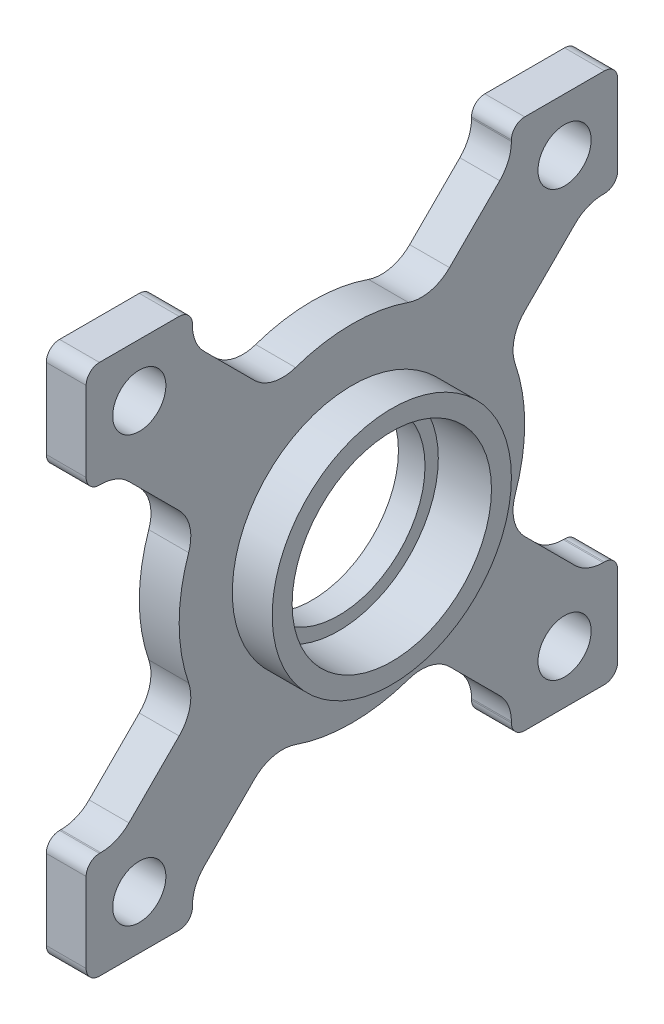
SolidWorks part; units mm, degrees
material "1350 合金"
ref_plane "前视基准面" through (0, 0, 0) normal (0, 0, 1) x (1, 0, 0)
ref_plane "上视基准面" through (0, 0, 0) normal (0, 1, 0) x (1, 0, 0)
ref_plane "右视基准面" through (0, 0, 0) normal (1, 0, 0) x (0, 0, -1)
sketch "草图1" plane through (0, 0, 0) normal (1, 0, 0) x (0, 0, -1)
  line L0 (0, 0) -> (40, -40) construction
  line L1 (1, 0) -> (7, 0)
  line L2 (0, -1) -> (0, -7)
  line L3 (1, -40) -> (7, -40)
  line L4 (40, -1) -> (40, -7)
  line L5 (40, 0) -> (0, -40) construction
  line L6 (4, -4) -> (4, -36) construction
  line L7 (4, -36) -> (36, -36) construction
  line L8 (36, -4) -> (36, -36) construction
  line L9 (4, -4) -> (36, -4) construction
  line L10 (3.2218, -8.8787) -> (6.9981, -12.6549)
  line L11 (31.1213, -3.2218) -> (27.3451, -6.9981)
  line L12 (8.8787, -3.2218) -> (12.6549, -6.9981)
  line L13 (36.7782, -8.8787) -> (33.0019, -12.6549)
  line L14 (33.0019, -27.3451) -> (36.7782, -31.1213)
  line L15 (8, -8) -> (8, -32) construction
  line L16 (2.8284, 2.8284) -> (42.8284, -37.1716) construction
  line L18 (37.1716, 2.8284) -> (-2.8284, -37.1716) construction
  line L19 (12.6549, -33.0019) -> (8.8787, -36.7782)
  line L20 (27.3451, -33.0019) -> (31.1213, -36.7782)
  line L21 (42.8284, -2.8284) -> (2.8284, -42.8284) construction
  line L22 (8, -32) -> (32, -32) construction
  line L23 (-2.8284, -2.8284) -> (37.1716, -42.8284) construction
  line L24 (32, -8) -> (32, -32) construction
  line L25 (8, -8) -> (32, -8) construction
  line L26 (1.1005, -8) -> (1, -8)
  line L27 (32, -1.1005) -> (32, -1)
  line L28 (33, 0) -> (39, 0)
  line L29 (1.1005, -32) -> (1, -32)
  line L30 (8, -38.8995) -> (8, -39)
  line L31 (32, -38.8995) -> (32, -39)
  line L32 (38.8995, -32) -> (39, -32)
  line L33 (38.8995, -8) -> (39, -8)
  line L34 (8, -1.1005) -> (8, -1)
  line L35 (40, -33) -> (40, -39)
  line L36 (0, 0) -> (40, 0) construction
  line L37 (33, -40) -> (39, -40)
  line L38 (40, 0) -> (40, -40) construction
  line L39 (0, -33) -> (0, -39)
  line L40 (0, -40) -> (40, -40) construction
  line L41 (6.9981, -27.3451) -> (3.2218, -31.1213)
  line L42 (0, 0) -> (0, -40) construction
  arc A0 (7.7124, -15.7557) -> (7.7124, -24.2443) centre (20, -20) ccw
  circle A1 centre (4, -4) radius 2
  circle A2 centre (36, -4) radius 2
  circle A3 centre (4, -36) radius 2
  circle A4 centre (36, -36) radius 2
  arc A5 (24.2443, -7.7124) -> (15.7557, -7.7124) centre (20, -20) ccw
  arc A6 (32.2876, -24.2443) -> (32.2876, -15.7557) centre (20, -20) ccw
  arc A7 (15.7557, -32.2876) -> (24.2443, -32.2876) centre (20, -20) ccw
  arc A8 (1, -32) -> (0, -33) centre (1, -33) ccw
  arc A9 (0, -39) -> (1, -40) centre (1, -39) ccw
  arc A10 (7, -40) -> (8, -39) centre (7, -39) ccw
  arc A11 (32, -39) -> (33, -40) centre (33, -39) ccw
  arc A12 (39, -40) -> (40, -39) centre (39, -39) ccw
  arc A13 (40, -33) -> (39, -32) centre (39, -33) ccw
  arc A14 (39, -8) -> (40, -7) centre (39, -7) ccw
  arc A15 (39, 0) -> (40, -1) centre (39, -1) cw
  arc A16 (33, 0) -> (32, -1) centre (33, -1) ccw
  arc A17 (8, -1) -> (7, 0) centre (7, -1) ccw
  arc A18 (1, -8) -> (0, -7) centre (1, -7) cw
  arc A19 (1, 0) -> (0, -1) centre (1, -1) ccw
  arc A20 (3.2218, -8.8787) -> (1.1005, -8) centre (1.1005, -11) ccw
  arc A21 (6.9981, -12.6549) -> (7.7124, -15.7557) centre (4.8768, -14.7763) cw
  arc A22 (7.7124, -24.2443) -> (6.9981, -27.3451) centre (4.8768, -25.2237) cw
  arc A23 (1.1005, -32) -> (3.2218, -31.1213) centre (1.1005, -29) ccw
  arc A24 (8.8787, -36.7782) -> (8, -38.8995) centre (11, -38.8995) ccw
  arc A25 (12.6549, -33.0019) -> (15.7557, -32.2876) centre (14.7763, -35.1232) cw
  arc A26 (27.3451, -33.0019) -> (24.2443, -32.2876) centre (25.2237, -35.1232) ccw
  arc A27 (31.1213, -36.7782) -> (32, -38.8995) centre (29, -38.8995) cw
  arc A28 (36.7782, -31.1213) -> (38.8995, -32) centre (38.8995, -29) ccw
  arc A29 (33.0019, -27.3451) -> (32.2876, -24.2443) centre (35.1232, -25.2237) cw
  arc A30 (33.0019, -12.6549) -> (32.2876, -15.7557) centre (35.1232, -14.7763) ccw
  arc A31 (36.7782, -8.8787) -> (38.8995, -8) centre (38.8995, -11) cw
  arc A32 (31.1213, -3.2218) -> (32, -1.1005) centre (29, -1.1005) ccw
  arc A33 (27.3451, -6.9981) -> (24.2443, -7.7124) centre (25.2237, -4.8768) cw
  arc A34 (12.6549, -6.9981) -> (15.7557, -7.7124) centre (14.7763, -4.8768) ccw
  arc A35 (8.8787, -3.2218) -> (8, -1.1005) centre (11, -1.1005) cw
  point P52 (0, -32)
  point P60 (32, -40)
  point P66 (40, -32)
  point P74 (32, 0)
  point P90 (2.3431, -32)
  point P95 (14.082, -31.5749)
  point P104 (31.5749, -25.918)
  point P113 (25.918, -8.4251)
  dimension "D3" = 26
  dimension "D5" = 4
  dimension "D6" = 4
  dimension "D7" = 4
  dimension "D8" = 4
  dimension "D13" = 1
  dimension "D15" = 3
  dimension "D1" = 40
  dimension "D2" = 40
  dimension "D4" = 4
  dimension "D11" = 4
  dimension "D14" = 2.3431
  dimension "D9" = 4
  dimension "D10" = 4
  dimension "D12" = 8
extrude "凸台-拉伸1" add sketch "草图1" along normal blind 3
sketch "草图2" plane through (3, 0, 0) normal (1, 0, 0) x (0, 0, -1)
  circle A0 centre (20, -20) radius 9
  dimension "D1" = 18
extrude "凸台-拉伸2" add sketch "草图2" along normal blind 3
sketch "草图3" plane through (6, 0, 0) normal (1, 0, 0) x (0, 0, -1)
  circle A0 centre (20, -20) radius 7.5
  dimension "D1" = 15
extrude "切除-拉伸1" cut sketch "草图3" against normal blind 4
sketch "草图4" plane through (2, 0, 0) normal (1, 0, 0) x (0, 0, -1)
  circle A0 centre (20, -20) radius 6.5
  dimension "D1" = 13
extrude "切除-拉伸2" cut sketch "草图4" against normal through all
